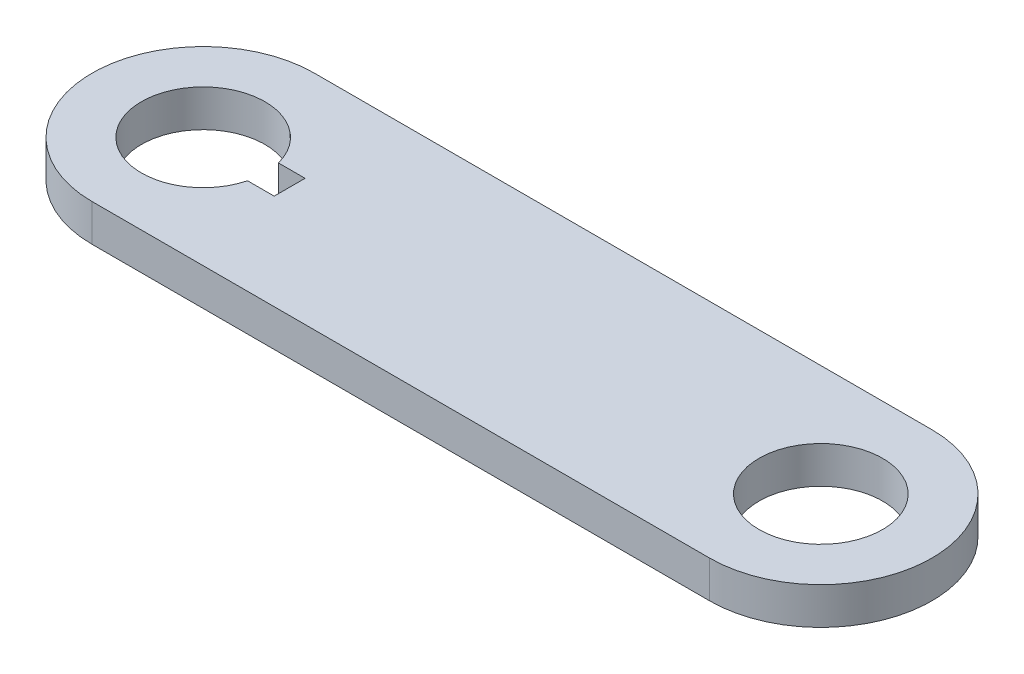
SolidWorks part; units mm, degrees
ref_plane "Front Plane" through (0, 0, 0) normal (0, 0, 1) x (1, 0, 0)
ref_plane "Top Plane" through (0, 0, 0) normal (0, 1, 0) x (1, 0, 0)
ref_plane "Right Plane" through (0, 0, 0) normal (1, 0, 0) x (0, 0, -1)
sketch "Sketch1" plane through (0, 0, 0) normal (0, 1, 0) x (1, 0, 0)
  line L0 (0, 0) -> (50, 0) construction
  line L1 (0, 9) -> (50, 9)
  line L2 (0, -9) -> (50, -9)
  line L4 (0, 1.25) -> (7, 1.25)
  line L5 (0, 1.25) -> (0, -1.25)
  line L6 (0, -1.25) -> (7, -1.25)
  line L7 (7, 1.25) -> (7, -1.25)
  arc A0 (0, 9) -> (0, -9) centre (0, 0) ccw
  arc A1 (50, -9) -> (50, 9) centre (50, 0) ccw
  arc A2 (4.8412, 1.25) -> (4.8412, -1.25) centre (0, 0) ccw
  circle A3 centre (50, 0) radius 5
  point P3 (25, 0)
  dimension "D3" = 10
  dimension "D4" = 10
  dimension "D1" = 50
  dimension "D2" = 9
  dimension "D5" = 7
  dimension "D6" = 2.5
extrude "Boss-Extrude1" add sketch "Sketch1" along normal mid plane 3
